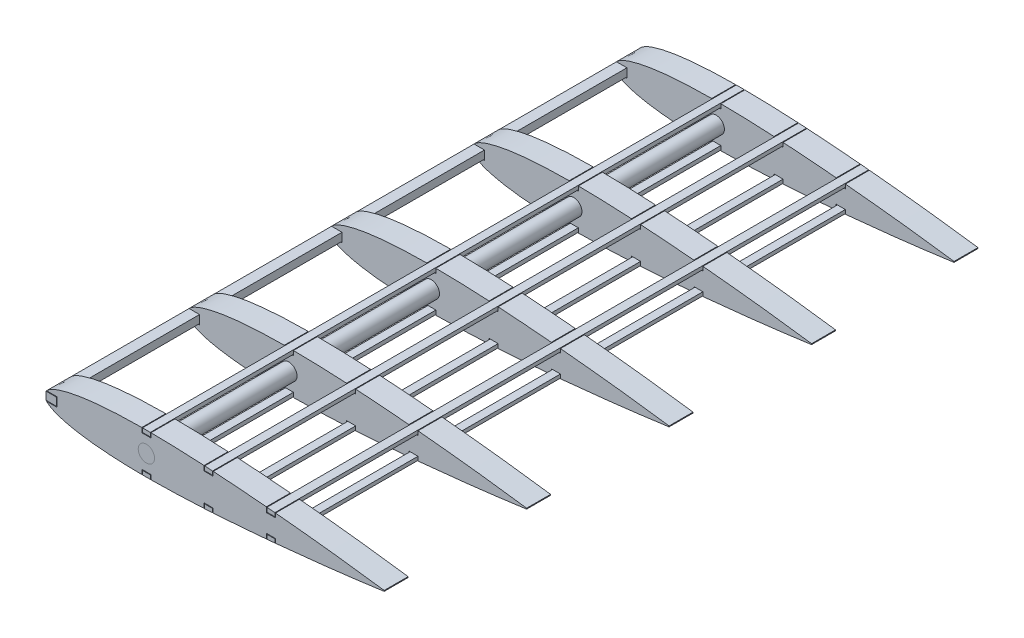
SolidWorks part; units mm, degrees
ref_plane "Front Plane" through (0, 0, 0) normal (0, 0, 1) x (1, 0, 0)
ref_plane "Top Plane" through (0, 0, 0) normal (0, 1, 0) x (1, 0, 0)
ref_plane "Right Plane" through (0, 0, 0) normal (1, 0, 0) x (0, 0, -1)
curve "Curve6"
  spline degree 3 poles (135, 0.1701, 0) (134.9737, 0.1738, 0) (134.8687, 0.1885, 0) (134.6326, 0.2216, 0) (134.2397, 0.2765, 0) (133.691, 0.3529, 0) (132.9876, 0.4499, 0) (132.1313, 0.5676, 0) (131.1241, 0.7048, 0) (129.9682, 0.8605, 0) (128.6665, 1.0342, 0) (127.2219, 1.2245, 0) (125.6379, 1.4305, 0) (123.918, 1.6507, 0) (122.0664, 1.8844, 0) (120.0873, 2.13, 0) (117.9854, 2.3862, 0) (115.7656, 2.652, 0) (113.4331, 2.9258, 0) (110.9933, 3.2062, 0) (108.4519, 3.4923, 0) (105.8149, 3.782, 0) (103.0884, 4.0747, 0) (100.2788, 4.3683, 0) (97.3926, 4.6621, 0) (94.4366, 4.9539, 0) (91.4177, 5.2429, 0) (88.3429, 5.5269, 0) (85.2195, 5.8051, 0) (82.0546, 6.0752, 0) (78.8558, 6.336, 0) (75.6304, 6.5857, 0) (72.3861, 6.8224, 0) (69.1303, 7.0447, 0) (65.8708, 7.2506, 0) (62.615, 7.4383, 0) (59.3707, 7.6063, 0) (56.1453, 7.7527, 0) (52.9463, 7.8759, 0) (49.7814, 7.9745, 0) (46.6579, 8.0468, 0) (43.583, 8.0914, 0) (40.5639, 8.1073, 0) (37.6077, 8.0933, 0) (34.7213, 8.0489, 0) (31.9114, 7.9727, 0) (29.1847, 7.8651, 0) (26.5473, 7.7253, 0) (24.0056, 7.5536, 0) (21.5654, 7.3502, 0) (19.2324, 7.1154, 0) (17.012, 6.8501, 0) (14.9095, 6.5553, 0) (12.9296, 6.2317, 0) (11.077, 5.8807, 0) (9.356, 5.5038, 0) (7.7705, 5.1023, 0) (6.324, 4.6779, 0) (5.0198, 4.232, 0) (3.8606, 3.7661, 0) (2.8487, 3.2817, 0) (1.986, 2.7797, 0) (1.2736, 2.261, 0) (0.7128, 1.7248, 0) (0.305, 1.1694, 0) (0.0557, 0.5922, 0) (-0.0271, 0, 0) (0.0557, -0.5922, 0) (0.305, -1.1694, 0) (0.7128, -1.7248, 0) (1.2736, -2.261, 0) (1.986, -2.7797, 0) (2.8487, -3.2817, 0) (3.8606, -3.7661, 0) (5.0198, -4.232, 0) (6.324, -4.6779, 0) (7.7705, -5.1023, 0) (9.356, -5.5038, 0) (11.077, -5.8807, 0) (12.9296, -6.2317, 0) (14.9095, -6.5553, 0) (17.012, -6.8501, 0) (19.2324, -7.1154, 0) (21.5654, -7.3502, 0) (24.0056, -7.5536, 0) (26.5473, -7.7253, 0) (29.1847, -7.8651, 0) (31.9114, -7.9727, 0) (34.7213, -8.0489, 0) (37.6077, -8.0933, 0) (40.5639, -8.1073, 0) (43.583, -8.0914, 0) (46.6579, -8.0468, 0) (49.7814, -7.9745, 0) (52.9463, -7.8759, 0) (56.1453, -7.7527, 0) (59.3707, -7.6063, 0) (62.615, -7.4383, 0) (65.8708, -7.2506, 0) (69.1303, -7.0447, 0) (72.3861, -6.8224, 0) (75.6304, -6.5857, 0) (78.8558, -6.336, 0) (82.0546, -6.0752, 0) (85.2195, -5.8051, 0) (88.3429, -5.5269, 0) (91.4177, -5.2429, 0) (94.4366, -4.9539, 0) (97.3926, -4.6621, 0) (100.2788, -4.3683, 0) (103.0884, -4.0747, 0) (105.8149, -3.782, 0) (108.4519, -3.4923, 0) (110.9933, -3.2062, 0) (113.4331, -2.9258, 0) (115.7656, -2.652, 0) (117.9854, -2.3862, 0) (120.0873, -2.13, 0) (122.0664, -1.8844, 0) (123.918, -1.6507, 0) (125.6379, -1.4305, 0) (127.2219, -1.2245, 0) (128.6665, -1.0342, 0) (129.9682, -0.8605, 0) (131.1241, -0.7048, 0) (132.1313, -0.5676, 0) (132.9876, -0.4499, 0) (133.691, -0.3529, 0) (134.2397, -0.2765, 0) (134.6326, -0.2216, 0) (134.8687, -0.1885, 0) (134.9737, -0.1738, 0) (135, -0.1701, 0) knots 0 0 0 0 0.000289 0.001156 0.002598 0.004612 0.007194 0.010336 0.014031 0.018272 0.023046 0.028343 0.03415 0.040454 0.047238 0.054489 0.062187 0.070314 0.078852 0.08778 0.097078 0.106722 0.116691 0.126961 0.137507 0.148306 0.159331 0.170556 0.181957 0.193504 0.205171 0.216932 0.228758 0.240621 0.252495 0.26435 0.276161 0.287898 0.299536 0.311047 0.322405 0.333584 0.344559 0.355306 0.3658 0.376018 0.385937 0.395538 0.404798 0.413699 0.422221 0.430349 0.438066 0.445357 0.452209 0.458612 0.464554 0.47003 0.475035 0.479569 0.483637 0.48725 0.490431 0.493219 0.495674 0.497891 0.5 0.502109 0.504326 0.506781 0.509569 0.51275 0.516363 0.520431 0.524965 0.52997 0.535446 0.541388 0.547791 0.554643 0.561934 0.569651 0.577779 0.586301 0.595202 0.604462 0.614063 0.623982 0.6342 0.644694 0.655441 0.666416 0.677595 0.688953 0.700464 0.712102 0.723839 0.73565 0.747505 0.759379 0.771242 0.783068 0.794829 0.806496 0.818043 0.829444 0.840669 0.851694 0.862493 0.873039 0.883309 0.893278 0.902922 0.91222 0.921148 0.929686 0.937813 0.945511 0.952762 0.959546 0.96585 0.971657 0.976954 0.981728 0.985969 0.989664 0.992806 0.995388 0.997402 0.998844 0.999711 1 1 1 1
sketch "Sketch4" plane through (0, 0, 0) normal (0, 0, 1) x (1, 0, 0)
  line L1 (135, 0) -> (0, 0) construction
  line L2 (135, -0.1701) -> (135, 0.1701)
  spline S0 degree 3 poles (914.6058, 4937.4453) (191.3357, -12.3963) (163.372, -3.7979) (134.6326, 0.2216) (134.2397, 0.2765) (133.691, 0.3529) (132.9876, 0.4499) (132.1313, 0.5676) (131.1241, 0.7048) (129.9682, 0.8605) (128.6665, 1.0342) (127.2219, 1.2245) (125.6379, 1.4305) (123.918, 1.6507) (122.0664, 1.8844) (120.0873, 2.13) (117.9854, 2.3862) (115.7656, 2.652) (113.4331, 2.9258) (110.9933, 3.2062) (108.4519, 3.4923) (105.8149, 3.782) (103.0884, 4.0747) (100.2788, 4.3683) (97.3926, 4.6621) (94.4366, 4.9539) (91.4177, 5.2429) (88.3429, 5.5269) (85.2195, 5.8051) (82.0546, 6.0752) (78.8558, 6.336) (75.6304, 6.5857) (72.3861, 6.8224) (69.1303, 7.0447) (65.8708, 7.2506) (62.615, 7.4383) (59.3707, 7.6063) (56.1453, 7.7527) (52.9463, 7.8759) (49.7814, 7.9745) (46.6579, 8.0468) (43.583, 8.0914) (40.5639, 8.1073) (37.6077, 8.0933) (34.7213, 8.0489) (31.9114, 7.9727) (29.1847, 7.8651) (26.5473, 7.7253) (24.0056, 7.5536) (21.5654, 7.3502) (19.2324, 7.1154) (17.012, 6.8501) (14.9095, 6.5553) (12.9296, 6.2317) (11.077, 5.8807) (9.356, 5.5038) (7.7705, 5.1023) (6.324, 4.6779) (5.0198, 4.232) (3.8606, 3.7661) (2.8487, 3.2817) (1.986, 2.7797) (1.2736, 2.261) (0.7128, 1.7248) (0.305, 1.1694) (0.0557, 0.5922) (-0.0271, 0) (0.0557, -0.5922) (0.305, -1.1694) (0.7128, -1.7248) (1.2736, -2.261) (1.986, -2.7797) (2.8487, -3.2817) (3.8606, -3.7661) (5.0198, -4.232) (6.324, -4.6779) (7.7705, -5.1023) (9.356, -5.5038) (11.077, -5.8807) (12.9296, -6.2317) (14.9095, -6.5553) (17.012, -6.8501) (19.2324, -7.1154) (21.5654, -7.3502) (24.0056, -7.5536) (26.5473, -7.7253) (29.1847, -7.8651) (31.9114, -7.9727) (34.7213, -8.0489) (37.6077, -8.0933) (40.5639, -8.1073) (43.583, -8.0914) (46.6579, -8.0468) (49.7814, -7.9745) (52.9463, -7.8759) (56.1453, -7.7527) (59.3707, -7.6063) (62.615, -7.4383) (65.8708, -7.2506) (69.1303, -7.0447) (72.3861, -6.8224) (75.6304, -6.5857) (78.8558, -6.336) (82.0546, -6.0752) (85.2195, -5.8051) (88.3429, -5.5269) (91.4177, -5.2429) (94.4366, -4.9539) (97.3926, -4.6621) (100.2788, -4.3683) (103.0884, -4.0747) (105.8149, -3.782) (108.4519, -3.4923) (110.9933, -3.2062) (113.4331, -2.9258) (115.7656, -2.652) (117.9854, -2.3862) (120.0873, -2.13) (122.0664, -1.8844) (123.918, -1.6507) (125.6379, -1.4305) (127.2219, -1.2245) (128.6665, -1.0342) (129.9682, -0.8605) (131.1241, -0.7048) (132.1313, -0.5676) (132.9876, -0.4499) (133.691, -0.3529) (134.2397, -0.2765) (134.6326, -0.2216) (163.3727, 3.798) (191.3371, 12.3968) (914.6589, -4937.8087) knots -0.313645 -0.313645 -0.313645 -0.313645 0.000289 0.001156 0.002598 0.004612 0.007194 0.010336 0.014031 0.018272 0.023046 0.028343 0.03415 0.040454 0.047238 0.054489 0.062187 0.070314 0.078852 0.08778 0.097078 0.106722 0.116691 0.126961 0.137507 0.148306 0.159331 0.170556 0.181957 0.193504 0.205171 0.216932 0.228758 0.240621 0.252495 0.26435 0.276161 0.287898 0.299536 0.311047 0.322405 0.333584 0.344559 0.355306 0.3658 0.376018 0.385937 0.395538 0.404798 0.413699 0.422221 0.430349 0.438066 0.445357 0.452209 0.458612 0.464554 0.47003 0.475035 0.479569 0.483637 0.48725 0.490431 0.493219 0.495674 0.497891 0.5 0.502109 0.504326 0.506781 0.509569 0.51275 0.516363 0.520431 0.524965 0.52997 0.535446 0.541388 0.547791 0.554643 0.561934 0.569651 0.577779 0.586301 0.595202 0.604462 0.614063 0.623982 0.6342 0.644694 0.655441 0.666416 0.677595 0.688953 0.700464 0.712102 0.723839 0.73565 0.747505 0.759379 0.771242 0.783068 0.794829 0.806496 0.818043 0.829444 0.840669 0.851694 0.862493 0.873039 0.883309 0.893278 0.902922 0.91222 0.921148 0.929686 0.937813 0.945511 0.952762 0.959546 0.96585 0.971657 0.976954 0.981728 0.985969 0.989664 0.992806 0.995388 0.997402 0.998844 0.999711 1.313652 1.313652 1.313652 1.313652 only from (135, 0.1701) to (135, -0.1701) construction
  spline S1 degree 3 poles (135, 0.1701) (134.9737, 0.1738) (134.8687, 0.1885) (134.6326, 0.2216) (134.2397, 0.2765) (133.691, 0.3529) (132.9876, 0.4499) (132.1313, 0.5676) (131.1241, 0.7048) (129.9682, 0.8605) (128.6665, 1.0342) (127.2219, 1.2245) (125.6379, 1.4305) (123.918, 1.6507) (122.0664, 1.8844) (120.0873, 2.13) (117.9854, 2.3862) (115.7656, 2.652) (113.4331, 2.9258) (110.9933, 3.2062) (108.4519, 3.4923) (105.8149, 3.782) (103.0884, 4.0747) (100.2788, 4.3683) (97.3926, 4.6621) (94.4366, 4.9539) (91.4177, 5.2429) (88.3429, 5.5269) (85.2195, 5.8051) (82.0546, 6.0752) (78.8558, 6.336) (75.6304, 6.5857) (72.3861, 6.8224) (69.1303, 7.0447) (65.8708, 7.2506) (62.615, 7.4383) (59.3707, 7.6063) (56.1453, 7.7527) (52.9463, 7.8759) (49.7814, 7.9745) (46.6579, 8.0468) (43.583, 8.0914) (40.5639, 8.1073) (37.6077, 8.0933) (34.7213, 8.0489) (31.9114, 7.9727) (29.1847, 7.8651) (26.5473, 7.7253) (24.0056, 7.5536) (21.5654, 7.3502) (19.2324, 7.1154) (17.012, 6.8501) (14.9095, 6.5553) (12.9296, 6.2317) (11.077, 5.8807) (9.356, 5.5038) (7.7705, 5.1023) (6.324, 4.6779) (5.0198, 4.232) (3.8606, 3.7661) (2.8487, 3.2817) (1.986, 2.7797) (1.2736, 2.261) (0.7128, 1.7248) (0.305, 1.1694) (0.0557, 0.5922) (-0.0271, 0) (0.0557, -0.5922) (0.305, -1.1694) (0.7128, -1.7248) (1.2736, -2.261) (1.986, -2.7797) (2.8487, -3.2817) (3.8606, -3.7661) (5.0198, -4.232) (6.324, -4.6779) (7.7705, -5.1023) (9.356, -5.5038) (11.077, -5.8807) (12.9296, -6.2317) (14.9095, -6.5553) (17.012, -6.8501) (19.2324, -7.1154) (21.5654, -7.3502) (24.0056, -7.5536) (26.5473, -7.7253) (29.1847, -7.8651) (31.9114, -7.9727) (34.7213, -8.0489) (37.6077, -8.0933) (40.5639, -8.1073) (43.583, -8.0914) (46.6579, -8.0468) (49.7814, -7.9745) (52.9463, -7.8759) (56.1453, -7.7527) (59.3707, -7.6063) (62.615, -7.4383) (65.8708, -7.2506) (69.1303, -7.0447) (72.3861, -6.8224) (75.6304, -6.5857) (78.8558, -6.336) (82.0546, -6.0752) (85.2195, -5.8051) (88.3429, -5.5269) (91.4177, -5.2429) (94.4366, -4.9539) (97.3926, -4.6621) (100.2788, -4.3683) (103.0884, -4.0747) (105.8149, -3.782) (108.4519, -3.4923) (110.9933, -3.2062) (113.4331, -2.9258) (115.7656, -2.652) (117.9854, -2.3862) (120.0873, -2.13) (122.0664, -1.8844) (123.918, -1.6507) (125.6379, -1.4305) (127.2219, -1.2245) (128.6665, -1.0342) (129.9682, -0.8605) (131.1241, -0.7048) (132.1313, -0.5676) (132.9876, -0.4499) (133.691, -0.3529) (134.2397, -0.2765) (134.6326, -0.2216) (134.8687, -0.1885) (134.9737, -0.1738) (135, -0.1701) knots 0 0 0 0 0.000289 0.001156 0.002598 0.004612 0.007194 0.010336 0.014031 0.018272 0.023046 0.028343 0.03415 0.040454 0.047238 0.054489 0.062187 0.070314 0.078852 0.08778 0.097078 0.106722 0.116691 0.126961 0.137507 0.148306 0.159331 0.170556 0.181957 0.193504 0.205171 0.216932 0.228758 0.240621 0.252495 0.26435 0.276161 0.287898 0.299536 0.311047 0.322405 0.333584 0.344559 0.355306 0.3658 0.376018 0.385937 0.395538 0.404798 0.413699 0.422221 0.430349 0.438066 0.445357 0.452209 0.458612 0.464554 0.47003 0.475035 0.479569 0.483637 0.48725 0.490431 0.493219 0.495674 0.497891 0.5 0.502109 0.504326 0.506781 0.509569 0.51275 0.516363 0.520431 0.524965 0.52997 0.535446 0.541388 0.547791 0.554643 0.561934 0.569651 0.577779 0.586301 0.595202 0.604462 0.614063 0.623982 0.6342 0.644694 0.655441 0.666416 0.677595 0.688953 0.700464 0.712102 0.723839 0.73565 0.747505 0.759379 0.771242 0.783068 0.794829 0.806496 0.818043 0.829444 0.840669 0.851694 0.862493 0.873039 0.883309 0.893278 0.902922 0.91222 0.921148 0.929686 0.937813 0.945511 0.952762 0.959546 0.96585 0.971657 0.976954 0.981728 0.985969 0.989664 0.992806 0.995388 0.997402 0.998844 0.999711 1 1 1 1
extrude "Boss-Extrude1" add sketch "Sketch4" along normal blind 6.35 and the other way blind 3.175
sketch "Sketch5" plane through (0, 0, 0) normal (0, 0, 1) x (1, 0, 0)
  line L1 (40.5, -8.1023) -> (40.5, 0) construction
  line L2 (38.6836, 6.2859) -> (42.3164, 6.2859)
  line L27 (38.6836, 6.2859) -> (38.6836, 9.9187)
  line L28 (38.6836, 9.9187) -> (42.3164, 9.9187)
  line L29 (90, -5.3734) -> (90, 0) construction
  line L42 (42.3164, 6.2859) -> (42.3164, 9.9187)
  line L43 (38.6836, 6.2859) -> (42.3164, 9.9187) construction
  line L44 (38.6836, 9.9187) -> (42.3164, 6.2859) construction
  line L49 (38.6836, -9.9187) -> (42.3164, -9.9187)
  line L50 (38.6836, -9.9187) -> (38.6836, -6.2859)
  line L55 (38.6836, -6.2859) -> (42.3164, -6.2859)
  line L56 (42.3164, -9.9187) -> (42.3164, -6.2859)
  line L57 (38.6836, -9.9187) -> (42.3164, -6.2859) construction
  line L62 (38.6836, -6.2859) -> (42.3164, -9.9187) construction
  line L63 (40.5, 0) -> (40.5, 8.1023) construction
  line L64 (-5, -1.8164) -> (5, -1.8164)
  line L65 (-5, -1.8164) -> (-5, 1.8164)
  line L66 (-5, 1.8164) -> (5, 1.8164)
  line L67 (5, -1.8164) -> (5, 1.8164)
  line L68 (-5, -1.8164) -> (5, 1.8164) construction
  line L69 (-5, 1.8164) -> (5, -1.8164) construction
  line L70 (88.1836, 3.557) -> (91.8164, 3.557)
  line L71 (88.1836, 3.557) -> (88.1836, 7.1898)
  line L72 (88.1836, 7.1898) -> (91.8164, 7.1898)
  line L73 (91.8164, 3.557) -> (91.8164, 7.1898)
  line L74 (88.1836, 3.557) -> (91.8164, 7.1898) construction
  line L75 (88.1836, 7.1898) -> (91.8164, 3.557) construction
  line L76 (88.1836, -7.1898) -> (91.8164, -7.1898)
  line L77 (88.1836, -7.1898) -> (88.1836, -3.557)
  line L78 (88.1836, -3.557) -> (91.8164, -3.557)
  line L79 (91.8164, -7.1898) -> (91.8164, -3.557)
  line L80 (88.1836, -7.1898) -> (91.8164, -3.557) construction
  line L81 (88.1836, -3.557) -> (91.8164, -7.1898) construction
  line L82 (90, 0) -> (90, 5.3734) construction
  line L83 (65.25, -7.2848) -> (65.25, 0) construction
  line L84 (63.4336, 5.4684) -> (67.0664, 5.4684)
  line L85 (63.4336, 5.4684) -> (63.4336, 9.1012)
  line L86 (63.4336, 9.1012) -> (67.0664, 9.1012)
  line L87 (67.0664, 5.4684) -> (67.0664, 9.1012)
  line L88 (63.4336, 5.4684) -> (67.0664, 9.1012) construction
  line L89 (63.4336, 9.1012) -> (67.0664, 5.4684) construction
  line L90 (63.4336, -9.1012) -> (67.0664, -9.1012)
  line L91 (63.4336, -9.1012) -> (63.4336, -5.4684)
  line L92 (63.4336, -5.4684) -> (67.0664, -5.4684)
  line L93 (67.0664, -9.1012) -> (67.0664, -5.4684)
  line L94 (63.4336, -9.1012) -> (67.0664, -5.4684) construction
  line L95 (63.4336, -5.4684) -> (67.0664, -9.1012) construction
  line L96 (65.25, 0) -> (65.25, 7.2848) construction
  circle A2 centre (40.5, 0) radius 3.24
  spline S2 degree 3 poles (135, 0.1701) (134.9737, 0.1738) (134.8687, 0.1885) (134.6326, 0.2216) (134.2397, 0.2765) (133.691, 0.3529) (132.9876, 0.4499) (132.1313, 0.5676) (131.1241, 0.7048) (129.9682, 0.8605) (128.6665, 1.0342) (127.2219, 1.2245) (125.6379, 1.4305) (123.918, 1.6507) (122.0664, 1.8844) (120.0873, 2.13) (117.9854, 2.3862) (115.7656, 2.652) (113.4331, 2.9258) (110.9933, 3.2062) (108.4519, 3.4923) (105.8149, 3.782) (103.0884, 4.0747) (100.2788, 4.3683) (97.3926, 4.6621) (94.4366, 4.9539) (91.4177, 5.2429) (88.3429, 5.5269) (85.2195, 5.8051) (82.0546, 6.0752) (78.8558, 6.336) (75.6304, 6.5857) (72.3861, 6.8224) (69.1303, 7.0447) (65.8708, 7.2506) (62.615, 7.4383) (59.3707, 7.6063) (56.1453, 7.7527) (52.9463, 7.8759) (49.7814, 7.9745) (46.6579, 8.0468) (43.583, 8.0914) (40.5639, 8.1073) (37.6077, 8.0933) (34.7213, 8.0489) (31.9114, 7.9727) (29.1847, 7.8651) (26.5473, 7.7253) (24.0056, 7.5536) (21.5654, 7.3502) (19.2324, 7.1154) (17.012, 6.8501) (14.9095, 6.5553) (12.9296, 6.2317) (11.077, 5.8807) (9.356, 5.5038) (7.7705, 5.1023) (6.324, 4.6779) (5.0198, 4.232) (3.8606, 3.7661) (2.8487, 3.2817) (1.986, 2.7797) (1.2736, 2.261) (0.7128, 1.7248) (0.305, 1.1694) (0.0557, 0.5922) (-0.0271, 0) (0.0557, -0.5922) (0.305, -1.1694) (0.7128, -1.7248) (1.2736, -2.261) (1.986, -2.7797) (2.8487, -3.2817) (3.8606, -3.7661) (5.0198, -4.232) (6.324, -4.6779) (7.7705, -5.1023) (9.356, -5.5038) (11.077, -5.8807) (12.9296, -6.2317) (14.9095, -6.5553) (17.012, -6.8501) (19.2324, -7.1154) (21.5654, -7.3502) (24.0056, -7.5536) (26.5473, -7.7253) (29.1847, -7.8651) (31.9114, -7.9727) (34.7213, -8.0489) (37.6077, -8.0933) (40.5639, -8.1073) (43.583, -8.0914) (46.6579, -8.0468) (49.7814, -7.9745) (52.9463, -7.8759) (56.1453, -7.7527) (59.3707, -7.6063) (62.615, -7.4383) (65.8708, -7.2506) (69.1303, -7.0447) (72.3861, -6.8224) (75.6304, -6.5857) (78.8558, -6.336) (82.0546, -6.0752) (85.2195, -5.8051) (88.3429, -5.5269) (91.4177, -5.2429) (94.4366, -4.9539) (97.3926, -4.6621) (100.2788, -4.3683) (103.0884, -4.0747) (105.8149, -3.782) (108.4519, -3.4923) (110.9933, -3.2062) (113.4331, -2.9258) (115.7656, -2.652) (117.9854, -2.3862) (120.0873, -2.13) (122.0664, -1.8844) (123.918, -1.6507) (125.6379, -1.4305) (127.2219, -1.2245) (128.6665, -1.0342) (129.9682, -0.8605) (131.1241, -0.7048) (132.1313, -0.5676) (132.9876, -0.4499) (133.691, -0.3529) (134.2397, -0.2765) (134.6326, -0.2216) (134.8687, -0.1885) (134.9737, -0.1738) (135, -0.1701) knots 0 0 0 0 0.000289 0.001156 0.002598 0.004612 0.007194 0.010336 0.014031 0.018272 0.023046 0.028343 0.03415 0.040454 0.047238 0.054489 0.062187 0.070314 0.078852 0.08778 0.097078 0.106722 0.116691 0.126961 0.137507 0.148306 0.159331 0.170556 0.181957 0.193504 0.205171 0.216932 0.228758 0.240621 0.252495 0.26435 0.276161 0.287898 0.299536 0.311047 0.322405 0.333584 0.344559 0.355306 0.3658 0.376018 0.385937 0.395538 0.404798 0.413699 0.422221 0.430349 0.438066 0.445357 0.452209 0.458612 0.464554 0.47003 0.475035 0.479569 0.483637 0.48725 0.490431 0.493219 0.495674 0.497891 0.5 0.502109 0.504326 0.506781 0.509569 0.51275 0.516363 0.520431 0.524965 0.52997 0.535446 0.541388 0.547791 0.554643 0.561934 0.569651 0.577779 0.586301 0.595202 0.604462 0.614063 0.623982 0.6342 0.644694 0.655441 0.666416 0.677595 0.688953 0.700464 0.712102 0.723839 0.73565 0.747505 0.759379 0.771242 0.783068 0.794829 0.806496 0.818043 0.829444 0.840669 0.851694 0.862493 0.873039 0.883309 0.893278 0.902922 0.91222 0.921148 0.929686 0.937813 0.945511 0.952762 0.959546 0.96585 0.971657 0.976954 0.981728 0.985969 0.989664 0.992806 0.995388 0.997402 0.998844 0.999711 1 1 1 1 construction
  spline S3 degree 3 poles (135, 0.1701) (134.9737, 0.1738) (134.8687, 0.1885) (134.6326, 0.2216) (134.2397, 0.2765) (133.691, 0.3529) (132.9876, 0.4499) (132.1313, 0.5676) (131.1241, 0.7048) (129.9682, 0.8605) (128.6665, 1.0342) (127.2219, 1.2245) (125.6379, 1.4305) (123.918, 1.6507) (122.0664, 1.8844) (120.0873, 2.13) (117.9854, 2.3862) (115.7656, 2.652) (113.4331, 2.9258) (110.9933, 3.2062) (108.4519, 3.4923) (105.8149, 3.782) (103.0884, 4.0747) (100.2788, 4.3683) (97.3926, 4.6621) (94.4366, 4.9539) (91.4177, 5.2429) (88.3429, 5.5269) (85.2195, 5.8051) (82.0546, 6.0752) (78.8558, 6.336) (75.6304, 6.5857) (72.3861, 6.8224) (69.1303, 7.0447) (65.8708, 7.2506) (62.615, 7.4383) (59.3707, 7.6063) (56.1453, 7.7527) (52.9463, 7.8759) (49.7814, 7.9745) (46.6579, 8.0468) (43.583, 8.0914) (40.5639, 8.1073) (37.6077, 8.0933) (34.7213, 8.0489) (31.9114, 7.9727) (29.1847, 7.8651) (26.5473, 7.7253) (24.0056, 7.5536) (21.5654, 7.3502) (19.2324, 7.1154) (17.012, 6.8501) (14.9095, 6.5553) (12.9296, 6.2317) (11.077, 5.8807) (9.356, 5.5038) (7.7705, 5.1023) (6.324, 4.6779) (5.0198, 4.232) (3.8606, 3.7661) (2.8487, 3.2817) (1.986, 2.7797) (1.2736, 2.261) (0.7128, 1.7248) (0.305, 1.1694) (0.0557, 0.5922) (-0.0271, 0) (0.0557, -0.5922) (0.305, -1.1694) (0.7128, -1.7248) (1.2736, -2.261) (1.986, -2.7797) (2.8487, -3.2817) (3.8606, -3.7661) (5.0198, -4.232) (6.324, -4.6779) (7.7705, -5.1023) (9.356, -5.5038) (11.077, -5.8807) (12.9296, -6.2317) (14.9095, -6.5553) (17.012, -6.8501) (19.2324, -7.1154) (21.5654, -7.3502) (24.0056, -7.5536) (26.5473, -7.7253) (29.1847, -7.8651) (31.9114, -7.9727) (34.7213, -8.0489) (37.6077, -8.0933) (40.5639, -8.1073) (43.583, -8.0914) (46.6579, -8.0468) (49.7814, -7.9745) (52.9463, -7.8759) (56.1453, -7.7527) (59.3707, -7.6063) (62.615, -7.4383) (65.8708, -7.2506) (69.1303, -7.0447) (72.3861, -6.8224) (75.6304, -6.5857) (78.8558, -6.336) (82.0546, -6.0752) (85.2195, -5.8051) (88.3429, -5.5269) (91.4177, -5.2429) (94.4366, -4.9539) (97.3926, -4.6621) (100.2788, -4.3683) (103.0884, -4.0747) (105.8149, -3.782) (108.4519, -3.4923) (110.9933, -3.2062) (113.4331, -2.9258) (115.7656, -2.652) (117.9854, -2.3862) (120.0873, -2.13) (122.0664, -1.8844) (123.918, -1.6507) (125.6379, -1.4305) (127.2219, -1.2245) (128.6665, -1.0342) (129.9682, -0.8605) (131.1241, -0.7048) (132.1313, -0.5676) (132.9876, -0.4499) (133.691, -0.3529) (134.2397, -0.2765) (134.6326, -0.2216) (134.8687, -0.1885) (134.9737, -0.1738) (135, -0.1701) knots 0 0 0 0 0.000289 0.001156 0.002598 0.004612 0.007194 0.010336 0.014031 0.018272 0.023046 0.028343 0.03415 0.040454 0.047238 0.054489 0.062187 0.070314 0.078852 0.08778 0.097078 0.106722 0.116691 0.126961 0.137507 0.148306 0.159331 0.170556 0.181957 0.193504 0.205171 0.216932 0.228758 0.240621 0.252495 0.26435 0.276161 0.287898 0.299536 0.311047 0.322405 0.333584 0.344559 0.355306 0.3658 0.376018 0.385937 0.395538 0.404798 0.413699 0.422221 0.430349 0.438066 0.445357 0.452209 0.458612 0.464554 0.47003 0.475035 0.479569 0.483637 0.48725 0.490431 0.493219 0.495674 0.497891 0.5 0.502109 0.504326 0.506781 0.509569 0.51275 0.516363 0.520431 0.524965 0.52997 0.535446 0.541388 0.547791 0.554643 0.561934 0.569651 0.577779 0.586301 0.595202 0.604462 0.614063 0.623982 0.6342 0.644694 0.655441 0.666416 0.677595 0.688953 0.700464 0.712102 0.723839 0.73565 0.747505 0.759379 0.771242 0.783068 0.794829 0.806496 0.818043 0.829444 0.840669 0.851694 0.862493 0.873039 0.883309 0.893278 0.902922 0.91222 0.921148 0.929686 0.937813 0.945511 0.952762 0.959546 0.96585 0.971657 0.976954 0.981728 0.985969 0.989664 0.992806 0.995388 0.997402 0.998844 0.999711 1 1 1 1 construction
  point P2 (40.5, 8.1023)
  point P9 (40.5, -8.1023)
  point P17 (0, 0)
  point P26 (90, 5.3734)
  point P31 (90, -5.3734)
  point P42 (65.25, 7.2848)
  point P47 (65.25, -7.2848)
  dimension "D1" = 6.48
  dimension "D2" = 3.6328
  dimension "D3" = 40.5
  dimension "D4" = 10
  dimension "D5" = 90
  dimension "D6" = 65.25
extrude "Cut-Extrude1" cut sketch "Sketch5" against normal through all and the other way through all
pattern_linear "LPattern1" count 5 spacing 56.6175 along (0, 0, 1) of bodies 107 101
sketch "Sketch8" plane through (0, 0, 0) normal (0, 0, 1) x (1, 0, 0)
  line L0 (5, -1.8164) -> (5, 1.8164) construction
  line L1 (0.6072, -1.5664) -> (4.75, -1.5664)
  line L3 (0.6072, 1.5664) -> (4.75, 1.5664)
  line L4 (4.75, -1.5664) -> (4.75, 1.5664)
  line L5 (0, 0) -> (4.75, 1.5664) construction
  line L6 (0, 0) -> (4.75, -1.5664) construction
  line L7 (5, 1.8164) -> (0.8248, 1.8164) construction
  line L8 (0.6072, -1.5664) -> (0.6072, 1.5664)
  line L9 (38.6836, 7.1913) -> (38.9336, 7.1913) construction
  line L10 (38.6836, 6.2859) -> (38.6836, 8.0968) construction
  line L11 (40.5, 6.2859) -> (40.5, 6.5359) construction
  line L12 (38.6836, 6.2859) -> (42.3164, 6.2859) construction
  line L13 (42.3164, 7.1913) -> (42.0664, 7.1913) construction
  line L14 (42.3164, 6.2859) -> (42.3164, 8.0968) construction
  line L15 (38.9336, 8.0982) -> (38.9336, 6.5359)
  line L16 (38.9336, 6.5359) -> (42.0664, 6.5359)
  line L17 (42.0664, 6.5359) -> (42.0664, 8.0982)
  line L18 (38.9336, 8.0982) -> (42.0664, 8.0982)
  line L19 (63.4336, 6.4291) -> (63.6836, 6.4291) construction
  line L20 (65.25, 5.4684) -> (65.25, 5.7184) construction
  line L21 (67.0664, 6.3213) -> (66.8164, 6.3213) construction
  line L22 (63.6836, 7.3757) -> (63.6836, 5.7184)
  line L23 (63.6836, 5.7184) -> (66.8164, 5.7184)
  line L24 (66.8164, 5.7184) -> (66.8164, 7.1897)
  line L25 (63.6836, 7.3757) -> (66.8164, 7.1897)
  line L26 (63.4336, 5.4684) -> (67.0664, 5.4684) construction
  line L27 (63.4336, 5.4684) -> (63.4336, 7.3898) construction
  line L28 (67.0664, 5.4684) -> (67.0664, 7.1742) construction
  line L29 (88.1836, 4.5483) -> (88.4336, 4.5483) construction
  line L30 (90, 3.557) -> (90, 3.807) construction
  line L31 (91.8164, 4.3803) -> (91.5664, 4.3803) construction
  line L32 (88.4336, 5.517) -> (88.4336, 3.807)
  line L33 (88.4336, 3.807) -> (91.5664, 3.807)
  line L34 (91.5664, 3.807) -> (91.5664, 5.2272)
  line L35 (88.4336, 5.517) -> (91.5664, 5.2272)
  line L36 (88.1836, 3.557) -> (88.1836, 5.5397) construction
  line L37 (88.1836, 3.557) -> (91.8164, 3.557) construction
  line L38 (91.8164, 3.557) -> (91.8164, 5.2036) construction
  line L39 (38.6836, -7.1913) -> (38.9336, -7.1913) construction
  line L40 (40.5, -6.5359) -> (40.5, -6.2859) construction
  line L41 (42.3164, -7.1913) -> (42.0664, -7.1913) construction
  line L42 (38.9336, -6.5359) -> (38.9336, -8.0982)
  line L43 (38.9336, -8.0982) -> (42.0664, -8.0982)
  line L44 (42.0664, -8.0982) -> (42.0664, -6.5359)
  line L45 (38.9336, -6.5359) -> (42.0664, -6.5359)
  line L46 (42.3164, -6.2859) -> (38.6836, -6.2859) construction
  line L47 (38.6836, -6.2859) -> (38.6836, -8.0968) construction
  line L48 (42.3164, -6.2859) -> (42.3164, -8.0968) construction
  line L49 (63.4336, -6.4291) -> (63.6836, -6.4291) construction
  line L50 (65.25, -5.7184) -> (65.25, -5.4684) construction
  line L51 (67.0664, -6.3213) -> (66.8164, -6.3213) construction
  line L52 (63.6836, -5.7184) -> (63.6836, -7.3757)
  line L53 (63.6836, -7.3757) -> (66.8164, -7.1897)
  line L54 (66.8164, -7.1897) -> (66.8164, -5.7184)
  line L55 (63.6836, -5.7184) -> (66.8164, -5.7184)
  line L56 (67.0664, -5.4684) -> (63.4336, -5.4684) construction
  line L57 (63.4336, -5.4684) -> (63.4336, -7.3898) construction
  line L58 (67.0664, -5.4684) -> (67.0664, -7.1742) construction
  line L59 (88.1836, -4.5483) -> (88.4336, -4.5483) construction
  line L60 (90, -3.807) -> (90, -3.557) construction
  line L61 (91.8164, -4.3803) -> (91.5664, -4.3803) construction
  line L62 (88.4336, -3.807) -> (88.4336, -5.517)
  line L63 (88.4336, -5.517) -> (91.5664, -5.2272)
  line L64 (91.5664, -5.2272) -> (91.5664, -3.807)
  line L65 (88.4336, -3.807) -> (91.5664, -3.807)
  line L66 (88.1836, -3.557) -> (88.1836, -5.5397) construction
  line L67 (91.8164, -3.557) -> (88.1836, -3.557) construction
  line L68 (91.8164, -3.557) -> (91.8164, -5.2036) construction
  circle A0 centre (40.5, 0) radius 3.24
  circle A1 centre (40.5, 0) radius 3.24 construction
  spline S0 degree 3 poles (135, 0.1701) (134.9737, 0.1738) (134.8687, 0.1885) (134.6326, 0.2216) (134.2397, 0.2765) (133.691, 0.3529) (132.9876, 0.4499) (132.1313, 0.5676) (131.1241, 0.7048) (129.9682, 0.8605) (128.6665, 1.0342) (127.2219, 1.2245) (125.6379, 1.4305) (123.918, 1.6507) (122.0664, 1.8844) (120.0873, 2.13) (117.9854, 2.3862) (115.7656, 2.652) (113.4331, 2.9258) (110.9933, 3.2062) (108.4519, 3.4923) (105.8149, 3.782) (103.0884, 4.0747) (100.2788, 4.3683) (97.3926, 4.6621) (94.4366, 4.9539) (91.4177, 5.2429) (88.3429, 5.5269) (85.2195, 5.8051) (82.0546, 6.0752) (78.8558, 6.336) (75.6304, 6.5857) (72.3861, 6.8224) (69.1303, 7.0447) (65.8708, 7.2506) (62.615, 7.4383) (59.3707, 7.6063) (56.1453, 7.7527) (52.9463, 7.8759) (49.7814, 7.9745) (46.6579, 8.0468) (43.583, 8.0914) (40.5639, 8.1073) (37.6077, 8.0933) (34.7213, 8.0489) (31.9114, 7.9727) (29.1847, 7.8651) (26.5473, 7.7253) (24.0056, 7.5536) (21.5654, 7.3502) (19.2324, 7.1154) (17.012, 6.8501) (14.9095, 6.5553) (12.9296, 6.2317) (11.077, 5.8807) (9.356, 5.5038) (7.7705, 5.1023) (6.324, 4.6779) (5.0198, 4.232) (3.8606, 3.7661) (2.8487, 3.2817) (1.986, 2.7797) (1.2736, 2.261) (0.7128, 1.7248) (0.305, 1.1694) (0.0557, 0.5922) (-0.0271, 0) (0.0557, -0.5922) (0.305, -1.1694) (0.7128, -1.7248) (1.2736, -2.261) (1.986, -2.7797) (2.8487, -3.2817) (3.8606, -3.7661) (5.0198, -4.232) (6.324, -4.6779) (7.7705, -5.1023) (9.356, -5.5038) (11.077, -5.8807) (12.9296, -6.2317) (14.9095, -6.5553) (17.012, -6.8501) (19.2324, -7.1154) (21.5654, -7.3502) (24.0056, -7.5536) (26.5473, -7.7253) (29.1847, -7.8651) (31.9114, -7.9727) (34.7213, -8.0489) (37.6077, -8.0933) (40.5639, -8.1073) (43.583, -8.0914) (46.6579, -8.0468) (49.7814, -7.9745) (52.9463, -7.8759) (56.1453, -7.7527) (59.3707, -7.6063) (62.615, -7.4383) (65.8708, -7.2506) (69.1303, -7.0447) (72.3861, -6.8224) (75.6304, -6.5857) (78.8558, -6.336) (82.0546, -6.0752) (85.2195, -5.8051) (88.3429, -5.5269) (91.4177, -5.2429) (94.4366, -4.9539) (97.3926, -4.6621) (100.2788, -4.3683) (103.0884, -4.0747) (105.8149, -3.782) (108.4519, -3.4923) (110.9933, -3.2062) (113.4331, -2.9258) (115.7656, -2.652) (117.9854, -2.3862) (120.0873, -2.13) (122.0664, -1.8844) (123.918, -1.6507) (125.6379, -1.4305) (127.2219, -1.2245) (128.6665, -1.0342) (129.9682, -0.8605) (131.1241, -0.7048) (132.1313, -0.5676) (132.9876, -0.4499) (133.691, -0.3529) (134.2397, -0.2765) (134.6326, -0.2216) (134.8687, -0.1885) (134.9737, -0.1738) (135, -0.1701) knots 0 0 0 0 0.000289 0.001156 0.002598 0.004612 0.007194 0.010336 0.014031 0.018272 0.023046 0.028343 0.03415 0.040454 0.047238 0.054489 0.062187 0.070314 0.078852 0.08778 0.097078 0.106722 0.116691 0.126961 0.137507 0.148306 0.159331 0.170556 0.181957 0.193504 0.205171 0.216932 0.228758 0.240621 0.252495 0.26435 0.276161 0.287898 0.299536 0.311047 0.322405 0.333584 0.344559 0.355306 0.3658 0.376018 0.385937 0.395538 0.404798 0.413699 0.422221 0.430349 0.438066 0.445357 0.452209 0.458612 0.464554 0.47003 0.475035 0.479569 0.483637 0.48725 0.490431 0.493219 0.495674 0.497891 0.5 0.502109 0.504326 0.506781 0.509569 0.51275 0.516363 0.520431 0.524965 0.52997 0.535446 0.541388 0.547791 0.554643 0.561934 0.569651 0.577779 0.586301 0.595202 0.604462 0.614063 0.623982 0.6342 0.644694 0.655441 0.666416 0.677595 0.688953 0.700464 0.712102 0.723839 0.73565 0.747505 0.759379 0.771242 0.783068 0.794829 0.806496 0.818043 0.829444 0.840669 0.851694 0.862493 0.873039 0.883309 0.893278 0.902922 0.91222 0.921148 0.929686 0.937813 0.945511 0.952762 0.959546 0.96585 0.971657 0.976954 0.981728 0.985969 0.989664 0.992806 0.995388 0.997402 0.998844 0.999711 1 1 1 1 construction
  point P0 (0, 0)
  point P41 (0, 0)
  dimension "D2" = 0.25
  dimension "D3" = 0.25
  dimension "D4" = 0.25
  dimension "D5" = 0.25
  dimension "D6" = 0.25
  dimension "D7" = 0.25
  dimension "D8" = 0.25
extrude "Boss-Extrude2" add sketch "Sketch8" along normal blind 232.825 and the other way blind 3.175
equation "\"Chord\"= 135mm"
equation "\"D1@Sketch5\"=\"Chord\"*0.4*12/100"
equation "\"D3@Sketch5\"=\"Chord\"*0.3"
equation "\"D4@Sketch5\"=\"Chord\"/13.5"
equation "\"D5@Sketch5\"=\"Chord\"*2/3"
equation "\"D6@Sketch5\"=\"Chord\"*(0.3+2/3)/2"
equation "\"D1@Sketch8\"=0.25"
